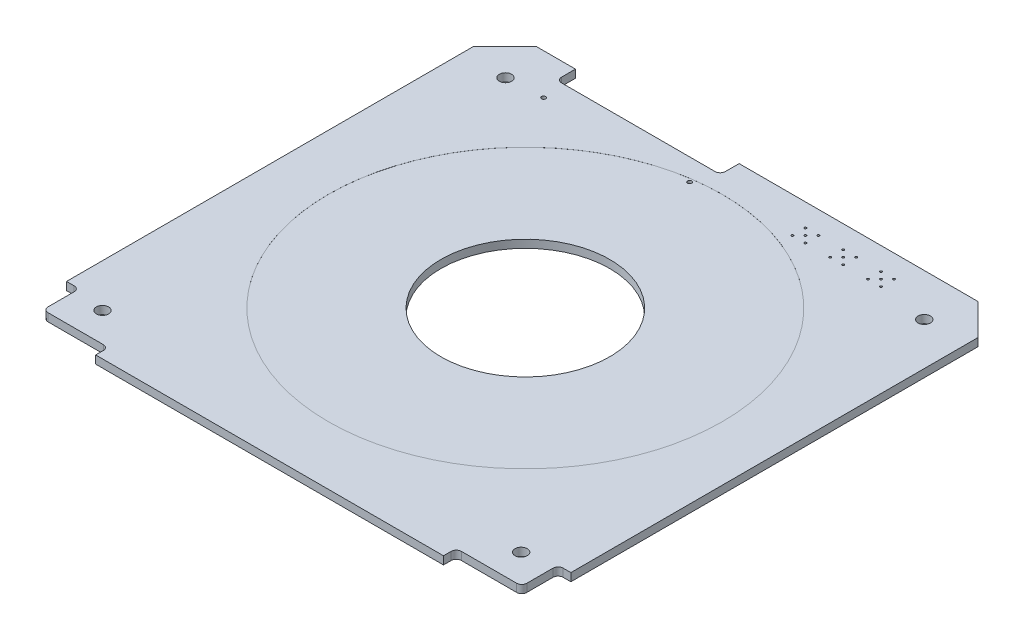
SolidWorks part; units mm, degrees
ref_plane "Front Plane" through (0, 0, 0) normal (0, 0, 1) x (1, 0, 0)
ref_plane "Top Plane" through (0, 0, 0) normal (0, 1, 0) x (1, 0, 0)
ref_plane "Right Plane" through (0, 0, 0) normal (1, 0, 0) x (0, 0, -1)
sketch "Sketch1" plane through (0, 0, 0) normal (0, 1, 0) x (1, 0, 0)
  line L0 (-49.3567, 41.6048) -> (-43.2567, 47.7048)
  line L1 (-34.0567, -47.5952) -> (33.9433, -47.5952)
  line L2 (-49.3567, -37.9952) -> (-49.3567, 41.6048)
  line L3 (-43.2567, 47.7048) -> (-35.5567, 47.7048)
  line L4 (49.2433, -37.9952) -> (49.2433, 41.6048)
  line L5 (-49.3567, -47.5952) -> (49.2979, 47.5386) construction
  line L6 (-49.3567, 47.7048) -> (49.2433, -47.5952) construction
  line L7 (-0.0567, 0.0548) -> (-0.0567, 47.7048) construction
  line L8 (49.2433, 41.6048) -> (43.1433, 47.7048)
  line L9 (-46.8567, -44.0952) -> (-46.8567, -38.9952)
  line L10 (-45.8567, -45.0952) -> (-35.0567, -45.0952)
  line L11 (46.7433, -44.0952) -> (46.7433, -38.9952)
  line L12 (-49.3567, -37.9952) -> (-47.8567, -37.9952)
  line L13 (-34.0567, -47.5952) -> (-34.0567, -46.0952)
  line L14 (33.9433, -47.5952) -> (33.9433, -46.0952)
  line L15 (49.2433, -37.9952) -> (47.7433, -37.9952)
  line L16 (34.9433, -45.0952) -> (45.7433, -45.0952)
  line L17 (-46.8567, -45.0952) -> (-46.8567, 41.6048) construction
  line L18 (46.7433, -45.0952) -> (46.7433, 41.6048) construction
  line L19 (-34.5567, 44.0048) -> (-4.5567, 44.0048)
  line L20 (-46.8567, -45.0952) -> (46.7433, -45.0952) construction
  line L21 (-49.3567, -47.5952) -> (49.2433, -47.5952) construction
  line L22 (-49.3567, -47.5952) -> (-49.3567, 41.6048) construction
  line L23 (49.2433, -47.5952) -> (49.2433, 41.6048) construction
  line L24 (-35.5567, 47.7048) -> (-35.5567, 45.0048)
  line L25 (-3.5567, 47.7048) -> (-3.5567, 45.0048)
  line L26 (-3.5567, 47.7048) -> (43.1433, 47.7048)
  line L27 (-43.2567, 44.0048) -> (43.1433, 44.0048) construction
  line L28 (21.2133, 40.7348) -> (23.7533, 40.7348) construction
  line L29 (-43.2567, 47.7048) -> (43.1433, 47.7048) construction
  line L30 (28.6133, 40.7348) -> (31.1533, 40.7348) construction
  line L31 (28.6133, 40.7348) -> (28.6133, 43.2748) construction
  line L32 (28.6133, 43.2748) -> (31.1533, 43.2748) construction
  line L33 (31.1533, 40.7348) -> (31.1533, 43.2748) construction
  line L34 (28.6133, 40.7348) -> (31.1533, 43.2748) construction
  line L35 (28.6133, 43.2748) -> (31.1533, 40.7348) construction
  line L36 (21.2133, 40.7348) -> (21.2133, 43.2748) construction
  line L37 (21.2133, 43.2748) -> (23.7533, 43.2748) construction
  line L38 (23.7533, 40.7348) -> (23.7533, 43.2748) construction
  line L39 (21.2133, 40.7348) -> (23.7533, 43.2748) construction
  line L40 (21.2133, 43.2748) -> (23.7533, 40.7348) construction
  line L41 (13.8133, 40.7348) -> (16.3533, 40.7348) construction
  line L42 (13.8133, 40.7348) -> (13.8133, 43.2748) construction
  line L43 (13.8133, 43.2748) -> (16.3533, 43.2748) construction
  line L44 (16.3533, 40.7348) -> (16.3533, 43.2748) construction
  line L45 (13.8133, 40.7348) -> (16.3533, 43.2748) construction
  line L46 (13.8133, 43.2748) -> (16.3533, 40.7348) construction
  arc A0 (47.7433, -37.9952) -> (46.7433, -38.9952) centre (47.7433, -38.9952) ccw
  arc A1 (34.9433, -45.0952) -> (33.9433, -46.0952) centre (34.9433, -46.0952) ccw
  arc A2 (-34.0567, -46.0952) -> (-35.0567, -45.0952) centre (-35.0567, -46.0952) ccw
  arc A3 (-46.8567, -38.9952) -> (-47.8567, -37.9952) centre (-47.8567, -38.9952) ccw
  arc A4 (46.7433, -44.0952) -> (45.7433, -45.0952) centre (45.7433, -44.0952) cw
  arc A5 (-45.8567, -45.0952) -> (-46.8567, -44.0952) centre (-45.8567, -44.0952) cw
  arc A6 (-4.5567, 44.0048) -> (-3.5567, 45.0048) centre (-4.5567, 45.0048) ccw
  arc A7 (-34.5567, 44.0048) -> (-35.5567, 45.0048) centre (-34.5567, 45.0048) cw
  circle A8 centre (-33.8267, 39.7448) radius 0.4
  circle A9 centre (-5.2767, 39.7448) radius 0.4
  circle A10 centre (29.8833, 42.0048) radius 0.2125
  circle A11 centre (28.6133, 43.2748) radius 0.2125
  circle A12 centre (31.1533, 43.2748) radius 0.2125
  circle A13 centre (31.1533, 40.7348) radius 0.2125
  circle A14 centre (28.6133, 40.7348) radius 0.2125
  circle A15 centre (22.4833, 42.0048) radius 0.2125
  circle A16 centre (21.2133, 43.2748) radius 0.2125
  circle A17 centre (23.7533, 43.2748) radius 0.2125
  circle A18 centre (23.7533, 40.7348) radius 0.2125
  circle A19 centre (21.2133, 40.7348) radius 0.2125
  circle A20 centre (15.0833, 42.0048) radius 0.2125
  circle A21 centre (13.8133, 43.2748) radius 0.2125
  circle A22 centre (16.3533, 43.2748) radius 0.2125
  circle A23 centre (16.3533, 40.7348) radius 0.2125
  circle A24 centre (13.8133, 40.7348) radius 0.2125
  point P0 (0, 0)
  point P26 (46.7433, -37.9952)
  point P29 (33.9433, -45.0952)
  point P32 (-34.0567, -45.0952)
  point P35 (-46.8567, -37.9952)
  dimension "D9" = 1
  dimension "D10" = 1
  dimension "D11" = 3.7
  dimension "D14" = 1
  dimension "D16" = 0.8
  dimension "D18" = 7.96
  dimension "D19" = 9.43
  dimension "D20" = 28.55
  dimension "D21" = 0.425
  dimension "D22" = 1.27
  dimension "D1" = 47.7048
  dimension "D2" = 98.6
  dimension "D3" = 6.1
  dimension "D4" = 6.1
  dimension "D5" = 95.3
  dimension "D6" = 2.5
  dimension "D7" = 85.7
  dimension "D8" = 15.3
  dimension "D12" = 13.8
  dimension "D13" = 32
  dimension "D15" = 137.1279
  dimension "D17" = 7.96
  dimension "D23" = 5.7
  dimension "D24" = 13.26
  dimension "D25" = 1.27
  dimension "D27" = 5.7
  dimension "D28" = 7.4
  dimension "D26" = 3
extrude "Boss-Extrude1" add sketch "Sketch1" along normal blind 1.56
sketch "Sketch7" plane through (0, 1.56, 0) normal (0, 1, 0) x (1, 0, 0)
  line L1 (-46.75, -45) -> (46.75, -45)
  line L2 (-46.75, -45) -> (-46.75, 45)
  line L3 (-46.75, 45) -> (46.75, 45)
  line L4 (46.75, -45) -> (46.75, 45)
  line L5 (-46.75, -45) -> (46.75, 45)
  line L6 (-46.75, 45) -> (46.75, -45)
  point P0 (0, 0)
  dimension "D1" = 90
  dimension "D2" = 93.5
hole_wizard "M2 Clearance Hole2" positions "Sketch9" profile "Sketch8" hole size "M2" standard "ANSI Metric"
sketch "Sketch9" plane through (0, 1.56, 0) normal (0, 1, 0) x (1, 0, 0)
  line L0 (-46.75, -45) -> (46.75, 45) construction
  line L1 (-46.75, 45) -> (46.75, -45) construction
  point P0 (-40.9295, 39.3974)
  point P2 (40.9295, 39.3974)
  point P4 (40.9295, -39.3974)
  point P6 (-40.9295, -39.3974)
  dimension "D1" = 56.81
  dimension "D2" = 56.81
  dimension "D3" = 56.81
  dimension "D4" = 56.81
sketch "Sketch8" plane through (-40.9295, 1.56, -39.3974) normal (1, 0, 0) x (0, 0, 1)
  line L0 (0, 0) -> (0, 38.821)
  line L1 (0, 38.821) -> (1.2, 38.1)
  line L2 (1.2, 38.1) -> (1.2, 0)
  line L5 (1.2, 0) -> (0, 0)
  line L10 (0, 38.821) -> (-1.2, 38.1) construction
  line L11 (0, -6.35) -> (0, 107.95) construction
  dimension "Hole Dia." = 2.4
  dimension "Hole Depth" = 38.1
  dimension "Drill Angle" = 118
sketch "Sketch2" plane through (0, 1.56, 0) normal (0, 1, 0) x (1, 0, 0)
  line L0 (-49.3567, 41.6048) -> (-49.3567, -37.9952) construction
  circle A0 centre (0, 2.3474) radius 38.5
  circle A1 centre (-40.9295, 39.3974) radius 1.2 construction
  dimension "D1" = 77
  dimension "D2" = 37.05
  dimension "D3" = 49.3567
extrude "Cut-Extrude1" cut sketch "Sketch2" against normal blind 0.01
sketch "Sketch10" plane through (0, 1.55, 0) normal (0, 1, 0) x (1, 0, 0)
  circle A0 centre (0, 2.3474) radius 16.5
  circle A1 centre (0, 2.3474) radius 38.5 construction
  dimension "D1" = 33
extrude "Cut-Extrude2" cut sketch "Sketch10" against normal blind 10
